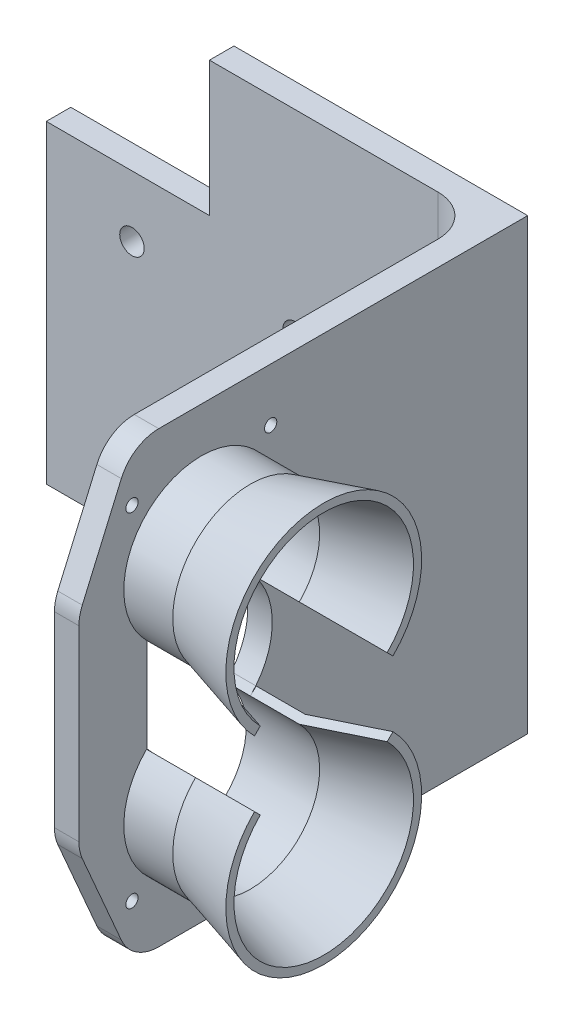
SolidWorks part; units mm, degrees
ref_plane "前视基准面" through (0, 0, 0) normal (0, 0, 1) x (1, 0, 0)
ref_plane "上视基准面" through (0, 0, 0) normal (0, 1, 0) x (1, 0, 0)
ref_plane "右视基准面" through (0, 0, 0) normal (1, 0, 0) x (0, 0, -1)
other "Configuration Table"
sketch "草图1" plane through (0, 0, 0) normal (0, 1, 0) x (1, 0, 0)
  line L0 (-30.1176, 27.2843) -> (25.8824, 27.2843)
  line L1 (25.8824, 27.2843) -> (25.8824, -27.7157)
  line L2 (25.8824, -27.7157) -> (22.8824, -27.7157)
  line L3 (22.8824, -27.7157) -> (22.8824, 24.2843)
  line L4 (22.8824, 24.2843) -> (-30.1176, 24.2843)
  line L5 (-30.1176, 24.2843) -> (-30.1176, 27.2843)
  dimension "D1" = 55
  dimension "D2" = 56
  dimension "D3" = 3
  dimension "D4" = 3
extrude "凸台-拉伸1" add sketch "草图1" along normal mid plane 55
ref_plane "基准面1" through (0, 0, -27.2843) normal (0, 0, -1) x (-1, 0, 0)
sketch "草图2" plane through (0, 0, -27.2843) normal (0, 0, -1) x (-1, 0, 0)
  line L0 (18.1176, -3.5) -> (1.1176, -3.5)
  line L1 (-25.8824, 27.5) -> (-25.8824, -27.5) construction
  line L2 (30.1176, 27.5) -> (30.1176, -27.5) construction
  line L3 (-25.8824, 27.5) -> (30.1176, 27.5) construction
  line L4 (30.1176, -11) -> (10.1176, -11)
  line L5 (10.1176, -11) -> (10.1176, -27.5)
  line L6 (-25.8824, -27.5) -> (30.1176, -27.5) construction
  line L7 (10.1176, -27.5) -> (30.1176, -27.5)
  line L8 (30.1176, -27.5) -> (30.1176, -11)
  line L9 (-25.8824, 0) -> (30.1176, 0)
  line L10 (10.1176, 27.5) -> (30.1176, 27.5)
  line L11 (10.1176, 11) -> (10.1176, 27.5)
  line L12 (30.1176, 11) -> (10.1176, 11)
  line L13 (30.1176, 27.5) -> (30.1176, 11)
  circle A2 centre (19.6176, -3.5) radius 1.5
  circle A3 centre (-0.3824, -3.5) radius 1.5
  circle A4 centre (19.6176, 3.5) radius 1.5
  circle A5 centre (-0.3824, 3.5) radius 1.5
  dimension "D3" = 3
  dimension "D4" = 3
  dimension "D1" = 31
  dimension "D2" = 31
  dimension "D5" = 10.5
  dimension "D6" = 25.5
  dimension "D7" = 7.5
  dimension "D8" = 20
ref_plane "基准面2" through (25.8824, 0, 0) normal (1, 0, 0) x (0, 0, -1)
sketch "草图3" plane through (25.8824, 0, 0) normal (1, 0, 0) x (0, 0, -1)
  line L0 (-27.7157, 27.5) -> (-27.7157, -27.5) construction
  line L1 (-22.7157, 22.5) -> (-2.7157, 22.5)
  line L2 (-22.7157, 22.5) -> (-22.7157, -22.5)
  line L3 (-22.7157, -22.5) -> (-2.7157, -22.5)
  line L4 (-2.7157, 22.5) -> (-2.7157, -22.5)
  line L5 (-22.7157, 22.5) -> (-2.7157, -22.5) construction
  line L6 (-22.7157, -22.5) -> (-2.7157, 22.5) construction
  line L7 (-12.7157, 22.5) -> (-12.7157, 22)
  line L8 (-12.7157, 12.5) -> (-6.7053, 6.4896)
  line L9 (-12.7157, 12.5) -> (-18.7261, 6.4896)
  line L10 (-12.7157, -12.5) -> (-18.7261, -6.4896)
  line L11 (-12.7157, -12.5) -> (-6.7053, -6.4896)
  line L12 (-12.7157, -22) -> (-12.7157, -22.5)
  line L13 (-12.7157, -4) -> (-12.7157, -21)
  line L14 (-12.7157, 3) -> (-12.7157, -3)
  line L15 (-12.7157, 21) -> (-12.7157, 4)
  line L16 (-22.7157, 0) -> (-2.7157, 0)
  line L17 (-18.7261, 6.4896) -> (-19.3945, 5.744)
  line L18 (-6.7053, 6.4896) -> (-6.0369, 5.744)
  line L19 (-6.7053, -6.4896) -> (-6.0369, -5.744)
  line L20 (-18.7261, -6.4896) -> (-19.3945, -5.744)
  line L21 (-19.3945, 5.744) -> (-19.3945, -5.744)
  line L23 (-27.7157, 27.5) -> (27.2843, 27.5) construction
  line L25 (-23.7833, 27.5) -> (-27.7157, 27.5)
  line L26 (-27.7157, 27.5) -> (-27.7157, 23.5676)
  line L27 (-27.7157, -23.5676) -> (-27.7157, -27.5)
  line L28 (-27.7157, -27.5) -> (-23.7833, -27.5)
  line L30 (-27.7157, 23.5676) -> (-27.7157, 20.2498)
  line L31 (-23.7833, 27.5) -> (-21.2157, 27.5)
  line L32 (-27.7157, -23.5676) -> (-27.7157, -20.2498)
  line L33 (-27.7157, -27.5) -> (-27.7157, -23.5676)
  line L35 (-23.7833, -27.5) -> (-21.2157, -27.5)
  line L36 (-21.2157, 27.5) -> (-27.7157, 12.5)
  line L37 (-27.7157, 12.5) -> (-27.7157, 20.2498)
  line L38 (-21.2157, -27.5) -> (-27.7157, -12.5)
  line L39 (-27.7157, -12.5) -> (-27.7157, -20.2498)
  circle A0 centre (-12.7157, 12.5) radius 8.5
  circle A1 centre (-12.7157, -12.5) radius 8.5
  arc A2 (-6.0369, 5.744) -> (-6.0369, -5.744) centre (-13.1949, 0) cw
  circle A4 centre (-12.7157, 12.5) radius 9.5
  circle A5 centre (-12.7157, -12.5) radius 9.5
  circle A6 centre (-4.2157, -21) radius 0.75
  circle A7 centre (-21.2157, -21) radius 0.75
  circle A8 centre (-4.2157, 21) radius 0.75
  circle A9 centre (-21.2157, 21) radius 0.75
  point P0 (0, 0)
  dimension "D6" = 17
  dimension "D7" = 17
  dimension "D8" = 19
  dimension "D9" = 19
  dimension "D11" = 1.5
  dimension "D1" = 45
  dimension "D2" = 20
  dimension "D3" = 5
  dimension "D4" = 10
  dimension "D5" = 10
  dimension "D10" = 1.5
  dimension "D12" = 1.5
extrude "切除-拉伸3" cut sketch "草图3" against normal blind 3
ref_plane "基准面3" through (32.8824, 0, 0) normal (1, 0, 0) x (0, 0, -1)
sketch "草图4" plane through (32.8824, 0, 0) normal (1, 0, 0) x (0, 0, -1)
  circle A0 centre (-12.7157, 12.5) radius 12
  circle A1 centre (-12.7157, 12.5) radius 11
ref_plane "基准面4" through (0, 0, 12.7157) normal (0, 0, 1) x (0, -1, 0)
sketch "草图5" plane through (0, 0, 12.7157) normal (0, 0, 1) x (0, -1, 0)
  line L0 (-3, 25.8824) -> (-22, 25.8824) construction
  line L2 (-3, 25.8824) -> (-22, 25.8824)
  line L4 (-3, 25.8824) -> (-22, 25.8824)
  line L6 (-22, 25.8824) -> (-21, 25.8824)
  line L9 (-12.5, 32.8824) -> (-12.5, 25.8824)
  line L10 (-21, 25.8824) -> (-21, 31.8824)
  line L12 (-22, 25.8824) -> (-22, 31.8824)
  line L14 (-21, 31.8824) -> (-23.5, 40.8824)
  line L15 (-23.5, 40.8824) -> (-24.5, 40.8824)
  line L16 (-24.5, 40.8824) -> (-22, 31.8824)
  dimension "D1" = 6
  dimension "D2" = 9
revolve "旋转1" add sketch "草图5" angle 135 about L9
mirror "镜向1" about plane through (0, 0, 0) normal (0, 1, 0) of "旋转1"
mirror "镜向2" about plane through (0, 0, 12.7157) normal (0, 0, 1) of "旋转1"
mirror "镜向3" about plane through (0, 0, 12.7157) normal (0, 0, 1) of "镜向1"
extrude "切除-拉伸4" cut sketch "草图2" against normal blind 3 contours L13 L10 L11 L12 | A5 | A4 | L8 L4 L5 L7
fillet "圆角1" radius 5 1 edges at (22.8824, 0, -24.2843)
fillet "圆角2" radius 5 4 edges at (24.3824, -27.5, 21.2157) (24.3824, -12.5, 27.7157) (24.3824, 12.5, 27.7157) (24.3824, 27.5, 21.2157)
